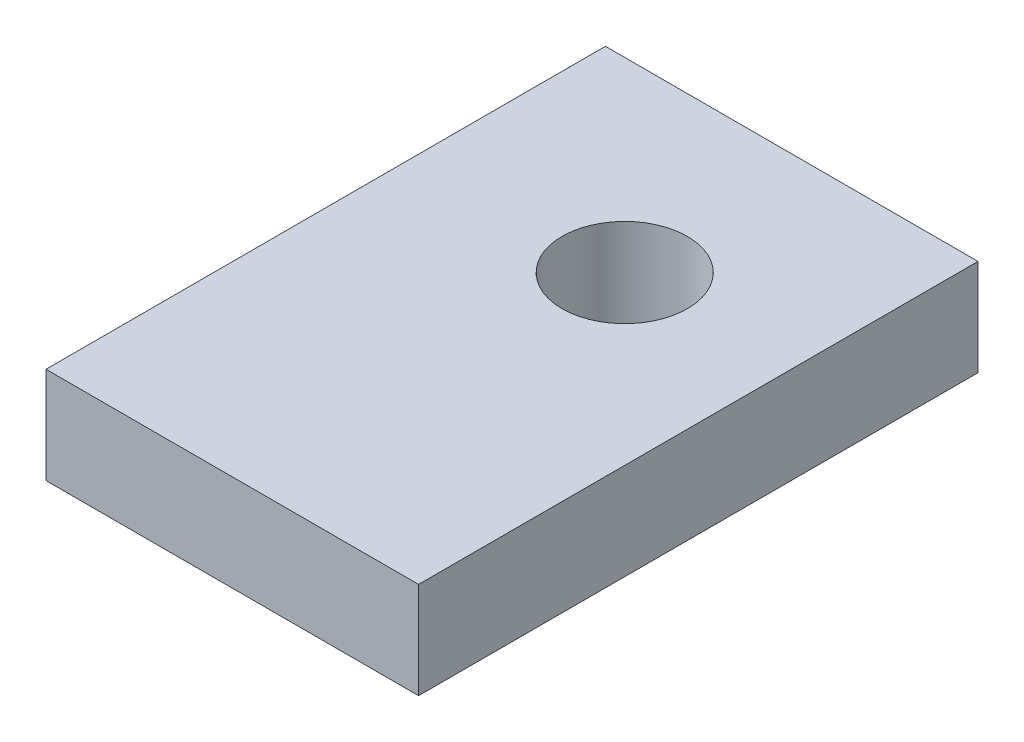
SolidWorks part; units mm, degrees
ref_plane "Front Plane" through (0, 0, 0) normal (0, 0, 1) x (1, 0, 0)
ref_plane "Top Plane" through (0, 0, 0) normal (0, 1, 0) x (1, 0, 0)
ref_plane "Right Plane" through (0, 0, 0) normal (1, 0, 0) x (0, 0, -1)
sketch "Sketch2" [suppressed] plane through (0, 0, 0) normal (1, 0, 0) x (0, 0, -1)
  line L1 (-33.67, 0) -> (0, 0)
  line L2 (0, 11.12) -> (-25.0712, 11.12) construction
  line L3 (-33.67, 7.945) -> (-19.7, 7.945) construction
  line L4 (0, 0) -> (0, 22.24)
  line L5 (0, 22.24) -> (-6.35, 22.24)
  line L6 (-6.35, 22.24) -> (-6.35, 0)
  line L7 (-6.35, 0) -> (0, 0)
  line L8 (0, 0) -> (0, 22.24) construction
  line L9 (0, 22.24) -> (-6.35, 22.24) construction
  line L10 (-6.35, 22.24) -> (-6.35, 0) construction
  line L11 (-6.35, 0) -> (0, 0) construction
  line L12 (-33.67, 7.945) -> (-33.67, 0) construction
  line L13 (-33.67, 0) -> (-19.7, 0) construction
  line L14 (-19.7, 7.945) -> (-19.7, 0) construction
  line L15 (-19.7, 14.295) -> (-19.7, 22.24) construction
  line L16 (-33.67, 22.24) -> (-19.7, 22.24) construction
  line L17 (-33.67, 14.295) -> (-33.67, 22.24) construction
  line L18 (-33.67, 14.295) -> (-19.7, 14.295) construction
  line L19 (-33.67, 0) -> (-33.67, 6.35)
  line L20 (-33.67, 6.35) -> (0, 6.35)
  line L21 (0, 0) -> (0, 6.35)
  point P16 (0, 11.12)
  dimension "D2" = 6.35
  dimension "D1" = 0
sketch "Sketch3" plane through (0, 0, 0) normal (0, 1, 0) x (1, 0, 0)
  line L0 (0, 0) -> (0, -36.845)
  line L1 (0, 0) -> (24.54, 0)
  line L4 (0, -36.845) -> (24.54, -36.845)
  line L7 (24.54, -36.845) -> (24.54, 0)
  line L8 (-432.66, -36.845) -> (24.54, -36.845) construction
  line L9 (24.54, -6.35) -> (24.54, 0) construction
  circle A0 centre (13.54, -12.27) radius 11 construction
  circle A1 centre (13.54, -12.27) radius 13.54 construction
  circle A2 centre (13.54, -12.27) radius 12.27 construction
  circle A3 centre (13.54, -12.27) radius 4 construction
  circle A6 centre (13.54, -12.27) radius 4.127
  point P10 (25.3083, -33.67)
  point P12 (24.54, 0)
  point P14 (25.2884, 0)
  point P22 (0, 0)
other "Pen Sketch1" parameters "D1"=19.9358, "D4"=5.8767, "D6"=40.1198, "D7"=5.8404, "D2"=2.54, "D3"=1.27, "D5"=6.35, "D8"=0.127
extrude "Boss-Extrude1" add sketch "Sketch3" along normal blind 6.35
